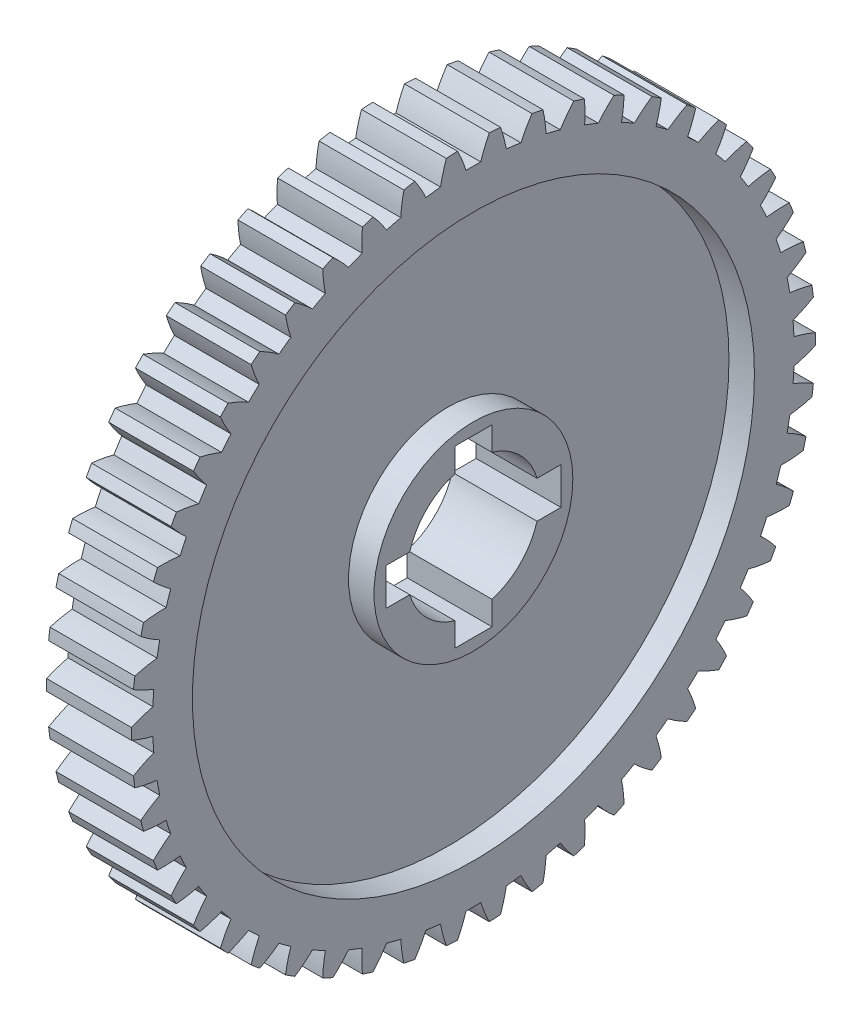
SolidWorks part; units mm, degrees
ref_plane "Plane1" through (0, 0, 0) normal (0, 0, 1) x (1, 0, 0)
ref_plane "Plane2" through (0, 0, 0) normal (0, 1, 0) x (1, 0, 0)
ref_plane "Plane3" through (0, 0, 0) normal (1, 0, 0) x (0, 0, -1)
sketch "HoldingSke" plane through (0, 0, 0) normal (0, 1, 0) x (1, 0, 0)
  line L0 (0, 0) -> (0.2571, -0.3064)
  line L1 (-15, 0) -> (100, 0) construction
  line L2 (0, 0) -> (-2.1039, 2.3779)
  line L3 (0, 0) -> (-11.863, 4.5341)
  line L4 (0, 0) -> (5.5511, 6.6156)
  line L5 (0, 0) -> (-46.8476, -17.4728)
  line L6 (0, 0) -> (-13.2634, -8.9489)
  line L7 (-2.1039, 2.3779) -> (8.6586, 51.2059)
  line L8 (-76.2, 54.61) -> (-72.9, 54.61)
  line L9 (-71.009, 38.7566) -> (-53.1078, 45.2721)
  line L10 (-76.2, 71.12) -> (104.1128, 71.12)
  line L11 (0, 0) -> (-16, 0)
  line L12 (-76.2, 101.6) -> (-76.122, 101.6)
  line L13 (24.9733, 27.94) -> (52.9534, 28.3307)
  line L14 (24.9733, 27.94) -> (24.9743, 27.94)
  line L15 (24.9733, 27.94) -> (100.4071, 29.2567)
  line L16 (-63.627, -2.5) -> (-12.827, -2.5)
  circle A0 centre (0, 0) radius 12.5
  circle A1 centre (0, 0) radius 37.5
  circle A2 centre (0, 0) radius 37.5
  circle A3 centre (0, 0) radius 12.5
  dimension "MHD" = 75
  dimension "Hub_dia" = 75
  dimension "Bore" = 25
  dimension "MBD" = 25
  dimension "Num_teeth" = 50
  dimension "Pitch" = 0.4
  dimension "Overall_len" = 50
  dimension "Show_teeth" = 50
  dimension "Thickness" = 16
  dimension "OAL" = 50.0001
  dimension "T_dim" = 3.3
  dimension "Ap" = 20
  dimension "H" = 19.05
  dimension "Pitch_radius" = 180.3128
  dimension "Width" = 16
  dimension "Backlash" = 0.078
  dimension "Addendum_fac" = 0.8
  dimension "Dedendum_fac" = 1
  dimension "Clearance_fac" = 0.2
  dimension "Dedendum_add" = 0.001
  dimension "Module" = 2.5
sketch "BasProSke" plane through (0, 0, 0) normal (0, 1, 0) x (1, 0, 0)
  line L0 (-10, 0) -> (60, 0) construction
  line L1 (0, 0) -> (0, 64.5)
  line L2 (0, 0) -> (16, 0)
  line L3 (16, 0) -> (16, 64.5)
  line L4 (16, 64.5) -> (0, 64.5)
  dimension "Thickness" = 16
  dimension "Diameter" = 129
revolve "Base-Revolve" add sketch "BasProSke" angle 360 about L0
sketch "TooCutSke" plane through (0, 0, 0) normal (1, 0, 0) x (0, 0, -1)
  line L1 (0, 0) -> (0, 107) construction
  line L2 (0, 0) -> (-2.0997, 62.4647) construction
  line L3 (0, 0) -> (-7.8455, 124.7) construction
  line L4 (-2.0997, 62.4647) -> (-3.9227, 62.35) construction
  arc A0 (1.3875, 60.4831) -> (-1.3875, 60.4831) centre (0, 0) ccw
  arc A1 (3.0147, 64.4549) -> (-3.0147, 64.4549) centre (0, 0) ccw
  circle A2 centre (0, 0) radius 62.5 construction
  circle A3 centre (0, 0) radius 58.7308 construction
  arc A4 (-1.3875, 60.4831) -> (-3.0147, 64.4549) centre (-25.2495, 53.0261) ccw
  arc A5 (3.0147, 64.4549) -> (1.3875, 60.4831) centre (25.2495, 53.0261) ccw
  dimension "Root_dia" = 120.998
  dimension "Overcut_dia" = 129.0508
  dimension "Pitch_dia" = 125
  dimension "Base_dia" = 117.4616
  dimension "Flank_rad" = 25
  dimension "Half_ang" = 3.6
  dimension "Half_CT" = 1.8267
extrude "ToothCut" cut sketch "TooCutSke" along normal through all
fillet "Breaks" [suppressed] radius 0.05
fillet "RootFillets" [suppressed] radius 0.501
pattern_circular "TeethCuts" count 50 every 7.2 about axis through (-10, 0, 0) along (1, 0, 0) of "ToothCut", "RootFillets", "Breaks"
sketch "HubNeaOneSke" plane through (0, 0, 0) normal (-1, 0, 0) x (0, 0, 1)
  circle A0 centre (0, 0) radius 37.5
  dimension "Diameter" = 75
extrude "HubNearOne" [suppressed] add sketch "HubNeaOneSke" along normal blind 34.0001
sketch "HubNeaBotSke" plane through (0, 0, 0) normal (-1, 0, 0) x (0, 0, 1)
  circle A0 centre (0, 0) radius 37.5
  dimension "Diameter" = 75
extrude "HubNearBoth" [suppressed] add sketch "HubNeaBotSke" along normal blind 17
ref_plane "FarPln" through (16, 0, 0) normal (1, 0, 0) x (0, 0, -1)
sketch "HubFarSke" plane through (16, 0, 0) normal (1, 0, 0) x (0, 0, -1)
  circle A0 centre (0, 0) radius 37.5
  dimension "Diameter" = 75
extrude "HubFar" [suppressed] add sketch "HubFarSke" along normal blind 17
sketch "BorSke" plane through (0, 0, 0) normal (1, 0, 0) x (0, 0, -1)
  circle A0 centre (0, 0) radius 12.5
  dimension "Diameter" = 25
extrude "Bore" cut sketch "BorSke" along normal mid plane 100.0001
sketch "KeySke" plane through (0, 0, 0) normal (1, 0, 0) x (0, 0, -1)
  line L0 (-4, 0) -> (-4, 15.8)
  line L1 (-4, 15.8) -> (4, 15.8)
  line L2 (4, 15.8) -> (4, 0)
  line L3 (0, 0) -> (0, 34) construction
  line L4 (-4, 0) -> (4, 0)
  dimension "Offset" = 15.8
  dimension "Width" = 8
extrude "Keyway" [suppressed] cut sketch "KeySke" along normal mid plane 100.0001
pattern_circular "Keyway2" [suppressed] count 2 every 90 about axis through (-10, 0, 0) along (1, 0, 0)
sketch "Sketch1" plane through (16, 0, 0) normal (1, 0, 0) x (0, 0, -1)
  circle A0 centre (0, 0) radius 12.5
  circle A1 centre (0, 0) radius 60.499
  circle A2 centre (0, 0) radius 18.75
  circle A3 centre (0, 0) radius 52.999
  dimension "D1" = 6.25
  dimension "D2" = 7.5
extrude "Cut-Extrude1" cut sketch "Sketch1" against normal blind 4.8 contours A3 | A2
sketch "Sketch2" plane through (0, 0, 0) normal (-1, 0, 0) x (0, 0, 1)
  circle A0 centre (0, 0) radius 12.5
  circle A1 centre (0, 0) radius 60.499
  circle A2 centre (0, 0) radius 52.999
  circle A3 centre (0, 0) radius 18.75
  dimension "D1" = 7.5
  dimension "D2" = 6.25
extrude "Cut-Extrude2" cut sketch "Sketch2" against normal blind 4.8 contours A2 A3
sketch "Sketch3" plane through (16, 0, 0) normal (1, 0, 0) x (0, 0, -1)
  line L0 (-12.5, 0) -> (12.5, 0)
  line L1 (0, 12.5) -> (0, -12.5)
  line L3 (-3.5, 8.5) -> (3.5, 8.5)
  line L4 (-3.5, 8.5) -> (-3.5, 16.5)
  line L5 (-3.5, 16.5) -> (3.5, 16.5)
  line L6 (3.5, 8.5) -> (3.5, 16.5)
  line L7 (-3.5, 8.5) -> (3.5, 16.5) construction
  line L8 (-3.5, 16.5) -> (3.5, 8.5) construction
  line L9 (-3.5, -8.5) -> (3.5, -8.5)
  line L10 (-3.5, -8.5) -> (-3.5, -16.5)
  line L11 (-3.5, -16.5) -> (3.5, -16.5)
  line L12 (3.5, -8.5) -> (3.5, -16.5)
  line L13 (-3.5, -8.5) -> (3.5, -16.5) construction
  line L14 (-3.5, -16.5) -> (3.5, -8.5) construction
  line L15 (-16.5, -3.5) -> (-8.5, -3.5)
  line L16 (-16.5, -3.5) -> (-16.5, 3.5)
  line L17 (-16.5, 3.5) -> (-8.5, 3.5)
  line L18 (-8.5, -3.5) -> (-8.5, 3.5)
  line L19 (-16.5, -3.5) -> (-8.5, 3.5) construction
  line L20 (-16.5, 3.5) -> (-8.5, -3.5) construction
  line L21 (8.5, -3.5) -> (16.5, -3.5)
  line L22 (8.5, -3.5) -> (8.5, 3.5)
  line L23 (8.5, 3.5) -> (16.5, 3.5)
  line L24 (16.5, -3.5) -> (16.5, 3.5)
  line L25 (8.5, -3.5) -> (16.5, 3.5) construction
  line L26 (8.5, 3.5) -> (16.5, -3.5) construction
  circle A0 centre (0, 0) radius 12.5 construction
  point P23 (0, 0)
  point P24 (0, 0)
  point P25 (0, 0)
  point P26 (0, 0)
  dimension "D1" = 8
  dimension "D2" = 7
  dimension "D3" = 7
extrude "Cut-Extrude4" cut sketch "Sketch3" against normal through all contours L16 L17 L18 L15 | L9 L12 L11 L10 | L21 L24 L23 L22 | L3 L6 L5 L4
equation "' \"Module@HoldingSke\" = 6.35"
equation "' \"Num_teeth@HoldingSke\" = 12"
equation "' \"Ap@HoldingSke\" =  20"
equation "' \"Ap@HoldingSke\" = 20"
equation "' \"Width@HoldingSke\" = 0.5 * 25.4"
equation "' \"Hub_dia@HoldingSke\"= 1 * 25.4"
equation "' \"Hub_dia@HoldingSke\" = 1 * 25.4"
equation "' \"Overall_len@HoldingSke\" = 1.0 * 25.4"
equation "' \"Bore@HoldingSke\" = 0.75 * 25.4"
equation "' \"T_dim@HoldingSke\" = 0.1 * 25.4"
equation "' \"Width@KeySke\" = 0.25 * 25.4"
equation "' \"Show_teeth@HoldingSke\" = 13"
equation "' \"Backlash@HoldingSke\" = 0.009 * 25.4"
equation "' \"Addendum_fac@HoldingSke\" = 1.0"
equation "' \"Dedendum_fac@HoldingSke\" = 1.25"
equation "' \"Dedendum_add@HoldingSke\" = 0.00005 * 25.4"
equation "' \"Clearance_fac@HoldingSke\" = 0.25"
equation "\"Pitch@HoldingSke\" = 1 / \"Module@HoldingSke\""
equation "\"Overcut_dia@TooCutSke\" = (\"Num_teeth@HoldingSke\" + 2 * \"Addendum_fac@HoldingSke\") / \"Pitch@HoldingSke\" + 0.002 * 25.4"
equation "\"Pitch_dia@TooCutSke\" = \"Num_teeth@HoldingSke\" / \"Pitch@HoldingSke\""
equation "\"Base_dia@TooCutSke\" = \"Num_teeth@HoldingSke\" / \"Pitch@HoldingSke\" * cos((\"Ap@HoldingSke\"  * 3.14159265 / 180))"
equation "\"Root_dia@TooCutSke\" = (\"Num_teeth@HoldingSke\" + 2) / \"Pitch@HoldingSke\" - 2 * (\"Addendum_fac@HoldingSke\" + \"Dedendum_fac@HoldingSke\") / \"Pitch@HoldingSke\" - \"Dedendum_add@HoldingSke\" * 2"
equation "\"Half_ang@TooCutSke\" = 180 / \"Num_teeth@HoldingSke\""
equation "\"Half_CT@TooCutSke\" = \"Num_teeth@HoldingSke\" / \"Pitch@HoldingSke\" * sin((3.14159265 / 2 / \"Num_teeth@HoldingSke\")) / 2 - 7 * \"Backlash@HoldingSke\" / 4"
equation "\"Flank_rad@TooCutSke\" = \"Num_teeth@HoldingSke\" / \"Pitch@HoldingSke\" / 5"
equation "\"Radius@RootFillets\" = \"Clearance_fac@HoldingSke\" / \"Pitch@HoldingSke\" + \"Dedendum_add@HoldingSke\""
equation "\"Break_rad@Breaks\" = 0.02 / \"Pitch@HoldingSke\""
equation "\"Thickness@HoldingSke\" = \"Width@HoldingSke\""
equation "\"OAL@HoldingSke\" = \"Thickness@HoldingSke\""
equation "\"MHD@HoldingSke\" = (\"Num_teeth@HoldingSke\" + 2) / \"Pitch@HoldingSke\" - 2 * (\"Addendum_fac@HoldingSke\" + \"Dedendum_fac@HoldingSke\")  / \"Pitch@HoldingSke\" - \"Dedendum_add@HoldingSke\" * 2"
equation "\"MBD@HoldingSke\" = (\"Num_teeth@HoldingSke\" + 2) / \"Pitch@HoldingSke\" - 2 * (\"Addendum_fac@HoldingSke\" + \"Dedendum_fac@HoldingSke\")  / \"Pitch@HoldingSke\" - \"Dedendum_add@HoldingSke\" * 2 - 0.002 * 25.4"
equation "\"MHD@HoldingSke\" = ((sgn( \"MHD@HoldingSke\" - \"Hub_dia@HoldingSke\" )-1)*( \"MHD@HoldingSke\" - \"Hub_dia@HoldingSke\" ))/-2+ \"Hub_dia@HoldingSke\""
equation "\"MBD@HoldingSke\" = ((sgn( \"MBD@HoldingSke\" - \"Bore@HoldingSke\" )-1)*( \"MBD@HoldingSke\" - \"Bore@HoldingSke\" ))/-2+ \"Bore@HoldingSke\""
equation "\"OAL@HoldingSke\" = ((sgn( \"OAL@HoldingSke\" - \"Overall_len@HoldingSke\" )+1)*( \"OAL@HoldingSke\" - \"Overall_len@HoldingSke\" ))/2 + \"Overall_len@HoldingSke\" + 0.000002 * 25.4"
equation "\"Num_teeth@TeethCuts\" = int( \"Show_teeth@HoldingSke\" ) + 1"
equation "\"Num_teeth@TeethCuts\" = ((sgn( \"Num_teeth@TeethCuts\" - \"Num_teeth@HoldingSke\" )-1)*( \"Num_teeth@TeethCuts\" - \"Num_teeth@HoldingSke\" ))/-2+ \"Num_teeth@HoldingSke\""
equation "\"Num_teeth@TeethCuts\" = ((sgn( \"Num_teeth@TeethCuts\" - 2.0)+1)*( \"Num_teeth@TeethCuts\" - 2.0))/2 +2.0"
equation "\"Angle@TeethCuts\" = 360.0 / \"Num_teeth@HoldingSke\""
equation "\"Diameter@BasProSke\" = (\"Num_teeth@HoldingSke\" + 2 * \"Addendum_fac@HoldingSke\") / \"Pitch@HoldingSke\""
equation "\"Thickness@BasProSke\"  = \"Thickness@HoldingSke\""
equation "' \"Fillet_rad@BasProSke\" =  \"Thickness@HoldingSke\" * 0.05"
equation "' \"Fillet_rad@BasProSke\" = \"Thickness@HoldingSke\" * 0.05"
equation "\"MHD@HoldingSke\" = ((sgn( \"MHD@HoldingSke\" - \"Root_dia@TooCutSke\" )-1)*( \"MHD@HoldingSke\" - \"Root_dia@TooCutSke\" ))/-2+ \"Root_dia@TooCutSke\""
equation "\"Diameter@HubNeaOneSke\" = \"MHD@HoldingSke\""
equation "\"Length@HubNearOne\" = \"OAL@HoldingSke\" - \"Thickness@BasProSke\""
equation "\"Diameter@HubNeaBotSke\" = \"MHD@HoldingSke\""
equation "\"Length@HubNearBoth\" = ( \"OAL@HoldingSke\" - \"Thickness@BasProSke\" ) / 2.0"
equation "\"Thickness@FarPln\" = \"Thickness@BasProSke\""
equation "\"Diameter@HubFarSke\" = \"MHD@HoldingSke\""
equation "\"Length@HubFar\" = ( \"OAL@HoldingSke\" - \"Thickness@BasProSke\" ) / 2.0"
equation "\"Diameter@BorSke\" = \"MBD@HoldingSke\""
equation "\"D1@Bore\" = \"OAL@HoldingSke\" * 2.0"
equation "\"D1@Keyway\" = \"OAL@HoldingSke\" * 2.0"
equation "\"Offset@KeySke\" = \"T_dim@HoldingSke\" + \"MBD@HoldingSke\" / 2.0"
